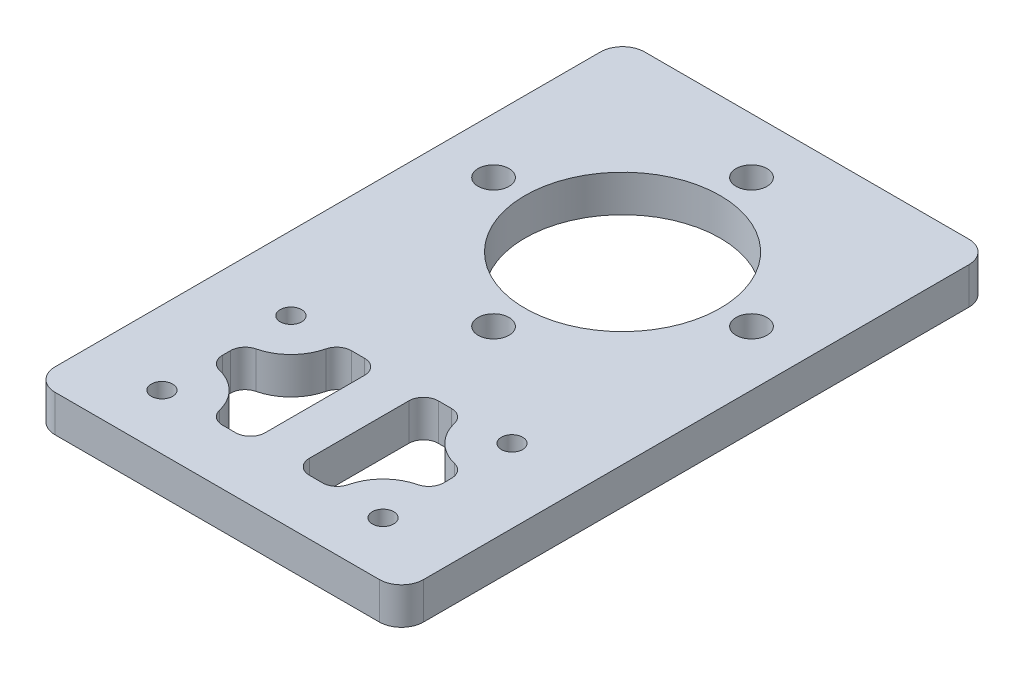
SolidWorks part; units mm, degrees
material "Thornel Mat VMA"
ref_plane "前视基准面" through (0, 0, 0) normal (0, 0, 1) x (1, 0, 0)
ref_plane "上视基准面" through (0, 0, 0) normal (0, 1, 0) x (1, 0, 0)
ref_plane "右视基准面" through (0, 0, 0) normal (1, 0, 0) x (0, 0, -1)
other "Configuration Table"
sketch "草图1" plane through (0, 0, 0) normal (0, 1, 0) x (1, 0, 0)
  line L1 (-25, -25) -> (25, -25)
  line L2 (-25, -25) -> (-25, 25)
  line L3 (-25, 25) -> (25, 25)
  line L4 (25, -25) -> (25, 25)
  line L5 (-25, -25) -> (25, 25) construction
  line L6 (-25, 25) -> (25, -25) construction
  circle A0 centre (0, 0) radius 21.05
  dimension "D1" = 42.1
  dimension "D2" = 50
  dimension "D3" = 50
extrude "凸台-拉伸1" add sketch "草图1" along normal blind 5
sketch "草图2" plane through (0, 5, 0) normal (0, 1, 0) x (1, 0, 0)
  line L0 (-25, 25) -> (-25, -25) construction
  line L1 (-25, -40) -> (25, -40) construction
  line L2 (-25, -40) -> (-25, -55)
  line L3 (-25, -55) -> (25, -55)
  line L4 (25, -40) -> (25, -55)
  line L5 (-25, -47.5) -> (25, -47.5) construction
  line L6 (25, -25) -> (25, 25) construction
  line L7 (-25, -25) -> (25, -25)
  line L9 (-25, -40) -> (25, -40) construction
  line L12 (-25, -25) -> (25, -25)
  line L13 (-25, -25) -> (-25, -40)
  line L14 (-25, -40) -> (25, -40) construction
  line L15 (25, -25) -> (25, -40)
  circle A0 centre (-15, -47.5) radius 1.45
  circle A1 centre (15, -47.5) radius 1.45
  dimension "D2" = 2.9
  dimension "D3" = 2.9
  dimension "D4" = 10
  dimension "D1" = 15
  dimension "D5" = 10
  dimension "D6" = 40
extrude "凸台-拉伸2" add sketch "草图2" against normal up to surface (5 mm away)
fillet "圆角1" radius 3 4 edges at (25, 2.5, 55) (-25, 2.5, 55) (25, 2.5, -25) (-25, 2.5, -25)
sketch "草图4" plane through (0, 5, 0) normal (0, 1, 0) x (1, 0, 0)
  circle A0 centre (0, 0) radius 21.05
extrude "凸台-拉伸3" add sketch "草图4" against normal up to surface (5 mm away) up to face at (0, 0, 15)
sketch "草图5" plane through (0, 0, 0) normal (0, -1, 0) x (1, 0, 0)
  circle A0 centre (0, 0) radius 13.25
  circle A1 centre (0, 0) radius 17.5 construction
  circle A2 centre (0, 17.5) radius 2.1
  circle A3 centre (17.5, 0) radius 2.1
  circle A4 centre (0, -17.5) radius 2.1
  circle A5 centre (-17.5, 0) radius 2.1
  dimension "D1" = 26.5
  dimension "D2" = 35
  dimension "D3" = 4.2
  dimension "D4" = 4
extrude "切除-拉伸2" cut sketch "草图5" against normal through all
sketch "草图6" plane through (0, 5, 0) normal (0, 1, 0) x (1, 0, 0)
  line L0 (0, 0) -> (0, -55) construction
  line L1 (-22, -55) -> (22, -55) construction
  line L2 (-15, -30) -> (15, -30) construction
  circle A0 centre (-15, -30) radius 1.45
  circle A1 centre (15, -30) radius 1.45
  dimension "D4" = 2.9
  dimension "D5" = 2.9
  dimension "D1" = 25
  dimension "D2" = 15
  dimension "D3" = 15
extrude "切除-拉伸3" cut sketch "草图6" against normal through all
sketch "草图7" plane through (0, 5, 0) normal (0, 1, 0) x (1, 0, 0)
  line L0 (-8.55, -30) -> (8.55, -30)
  line L1 (15, -36.45) -> (15, -41.05)
  line L2 (8.55, -47.5) -> (-8.55, -47.5)
  line L3 (-15, -36.45) -> (-15, -41.05)
  circle A0 centre (-15, -30) radius 6.45
  circle A1 centre (-15, -30) radius 1.45
  circle A2 centre (-15, -30) radius 1.45
  circle A3 centre (0, 0) radius 13.25
  circle A4 centre (0, 0) radius 13.25
  circle A5 centre (17.5, 0) radius 2.1
  circle A6 centre (17.5, 0) radius 2.1
  circle A7 centre (0, 17.5) radius 2.1
  circle A8 centre (0, 17.5) radius 2.1
  circle A9 centre (-17.5, 0) radius 2.1
  circle A10 centre (-17.5, 0) radius 2.1
  circle A11 centre (0, -17.5) radius 2.1
  circle A12 centre (0, -17.5) radius 2.1
  circle A13 centre (15, -30) radius 1.45
  circle A14 centre (15, -30) radius 1.45
  circle A15 centre (-15, -47.5) radius 1.45
  circle A16 centre (-15, -47.5) radius 1.45
  circle A17 centre (15, -47.5) radius 1.45
  circle A18 centre (15, -47.5) radius 1.45
  circle A19 centre (15, -30) radius 6.45
  circle A20 centre (15, -47.5) radius 6.45
  circle A21 centre (-15, -47.5) radius 6.45
  dimension "D1" = 0
  dimension "D2" = 0
  dimension "D3" = 0
  dimension "D4" = 0
  dimension "D5" = 0
  dimension "D6" = 0
  dimension "D7" = 0
  dimension "D8" = 0
  dimension "D9" = 0
  dimension "D10" = 5
extrude "切除-拉伸4" cut sketch "草图7" against normal through all contours A21 L2 A20 L1 A19 L0 A0 L3
sketch "草图8" plane through (0, 5, 0) normal (0, 1, 0) x (1, 0, 0)
  line L0 (0, -30) -> (0, -47.5) construction
  line L1 (-8.55, -30) -> (8.55, -30) construction
  line L2 (8.55, -47.5) -> (-8.55, -47.5) construction
  line L3 (-3, -30) -> (-3, -47.5)
  line L4 (3, -30) -> (3, -47.5)
  line L5 (-3, -30) -> (3, -30)
  line L6 (-3, -47.5) -> (3, -47.5)
  dimension "D1" = 3
  dimension "D2" = 3
extrude "凸台-拉伸4" add sketch "草图8" against normal blind 5
fillet "圆角2" radius 2 12 edges at (-8.55, 2.5, 47.5) (8.55, 2.5, 47.5) (15, 2.5, 41.05) (15, 2.5, 36.45) (-8.55, 2.5, 30) (-15, 2.5, 36.45) (-15, 2.5, 41.05) (8.55, 2.5, 30) (-3, 2.5, 30) (-3, 2.5, 47.5) (3, 2.5, 30) (3, 2.5, 47.5)
